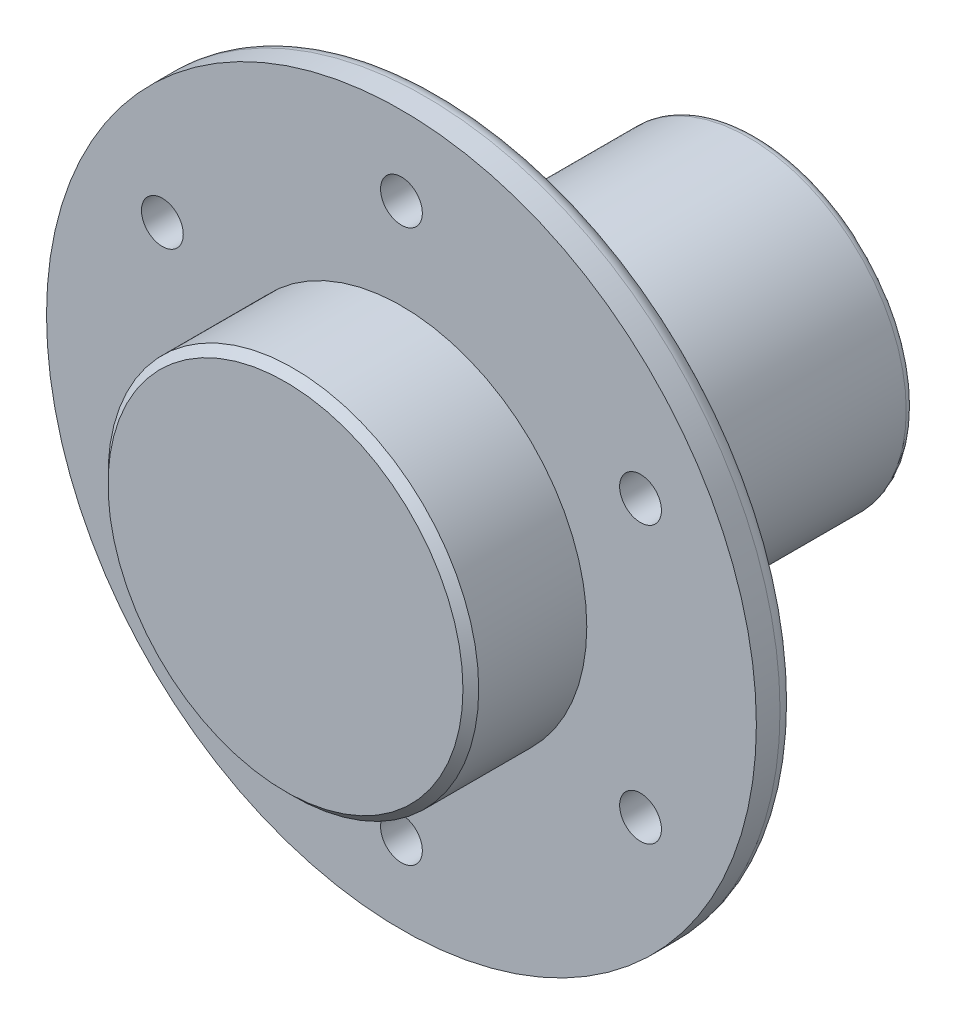
SolidWorks part; units mm, degrees
ref_plane "Front Plane" through (0, 0, 0) normal (0, 0, 1) x (1, 0, 0)
ref_plane "Top Plane" through (0, 0, 0) normal (0, 1, 0) x (1, 0, 0)
ref_plane "Right Plane" through (0, 0, 0) normal (1, 0, 0) x (0, 0, -1)
sketch "Sketch1" plane through (0, 0, 0) normal (0, 0, 1) x (1, 0, 0)
  circle A0 centre (0, 0) radius 20
  dimension "D1" = 40
extrude "Boss-Extrude1" add sketch "Sketch1" along normal blind 40
sketch "Sketch2" plane through (0, 0, 0) normal (0, 0, -1) x (-1, 0, 0)
  line L1 (-10.642, 10.642) -> (10.642, 10.642)
  line L2 (-10.642, 10.642) -> (-10.642, -10.642)
  line L3 (-10.642, -10.642) -> (10.642, -10.642)
  line L4 (10.642, 10.642) -> (10.642, -10.642)
  line L5 (-10.642, 10.642) -> (10.642, -10.642) construction
  line L6 (-10.642, -10.642) -> (10.642, 10.642) construction
  circle A0 centre (0, 0) radius 15.05
  point P0 (0, 0)
  dimension "D1" = 30.1
extrude "Cut-Extrude1" cut sketch "Sketch2" against normal blind 15 contours L4 L1 L2 L3
chamfer "Chamfer1" distance 0.8 angle 45 4 edges at (0, -10.642, 0) (-10.642, 0, 0) (0, 10.642, 0) (10.642, 0, 0)
sketch "Sketch3" plane through (0, 0, 40) normal (0, 0, 1) x (1, 0, 0)
  circle A0 centre (0, 0) radius 45
  dimension "D1" = 90
extrude "Boss-Extrude2" add sketch "Sketch3" along normal blind 5
sketch "Sketch4" plane through (0, 0, 45) normal (0, 0, 1) x (1, 0, 0)
  circle A0 centre (0, 0) radius 23.5
  dimension "D1" = 47
extrude "Boss-Extrude3" add sketch "Sketch4" along normal blind 14.7
chamfer "Chamfer2" distance 1 angle 45 1 edges at (23.5, 0, 59.7)
fillet "Fillet1" radius 2 1 edges at (45, 0, 40)
fillet "Fillet2" radius 8 1 edges at (20, 0, 40)
sketch "Sketch5" plane through (0, 0, 45) normal (0, 0, 1) x (1, 0, 0)
  line L0 (0, -1000) -> (0, 49000) construction
  circle A0 centre (0, 0) radius 35 construction
  circle A1 centre (0, 35) radius 2.65
  dimension "D1" = 70
  dimension "D2" = 5.3
extrude "Cut-Extrude2" cut sketch "Sketch5" against normal through all
pattern_circular "CirPattern1" count 6 over 360 about axis through (0, 0, 0) along (0, 0, 1) of "Cut-Extrude2"
fillet "Fillet3" radius 1 1 edges at (20, 0, 0)
